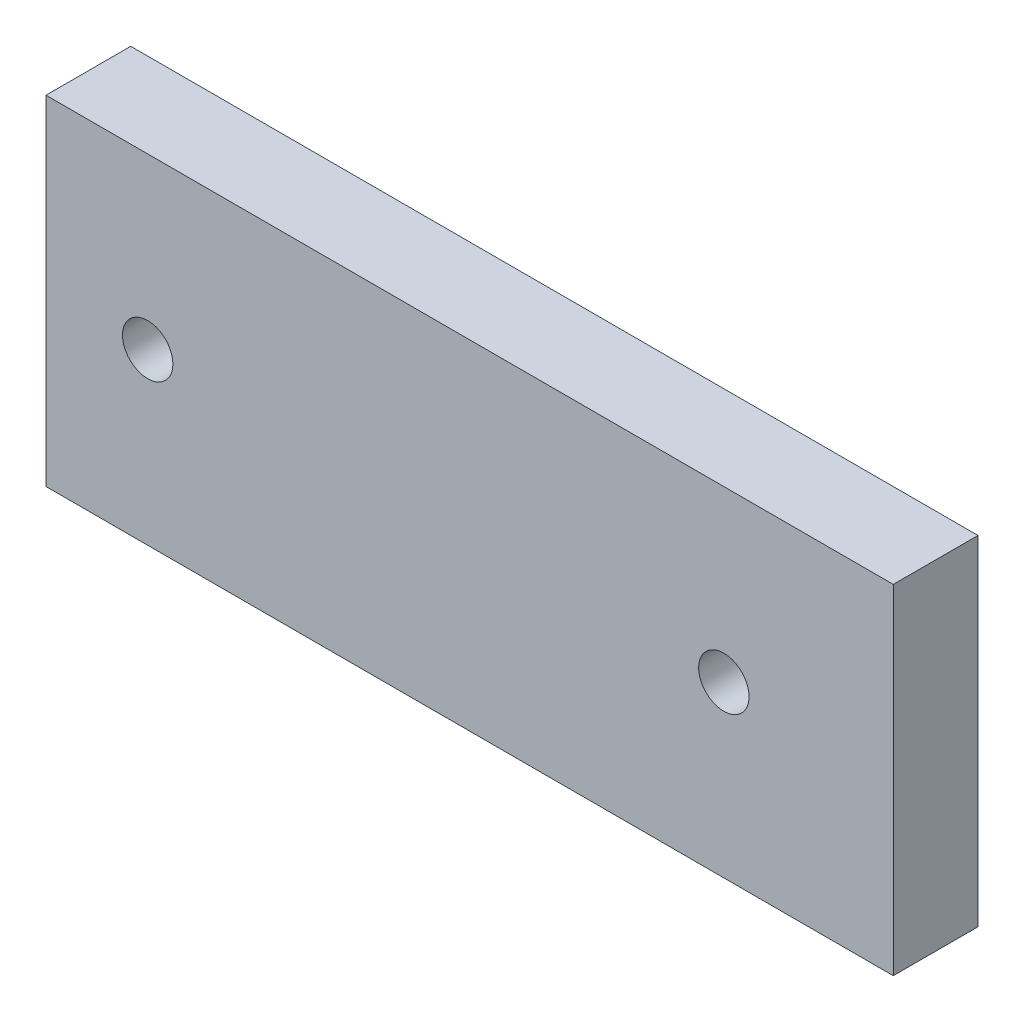
SolidWorks part; units mm, degrees
ref_plane "Front Plane" through (0, 0, 0) normal (0, 0, 1) x (1, 0, 0)
ref_plane "Top Plane" through (0, 0, 0) normal (0, 1, 0) x (1, 0, 0)
ref_plane "Right Plane" through (0, 0, 0) normal (1, 0, 0) x (0, 0, -1)
sketch "Sketch1" plane through (0, 0, 0) normal (0, 0, 1) x (1, 0, 0)
  line L1 (-25, 10) -> (25, 10)
  line L2 (-25, 10) -> (-25, -10)
  line L3 (-25, -10) -> (25, -10)
  line L4 (25, 10) -> (25, -10)
  circle A0 centre (-19, 0) radius 1.4857
  circle A1 centre (15, 0) radius 1.4857
  point P4 (-25, 0)
  point P7 (0, 10)
  point P12 (0, 0)
  point P13 (0, 0)
  dimension "D1" = 20
  dimension "D2" = 50
  dimension "D3" = 19
  dimension "D4" = 15
extrude "Boss-Extrude1" add sketch "Sketch1" against normal blind 5
